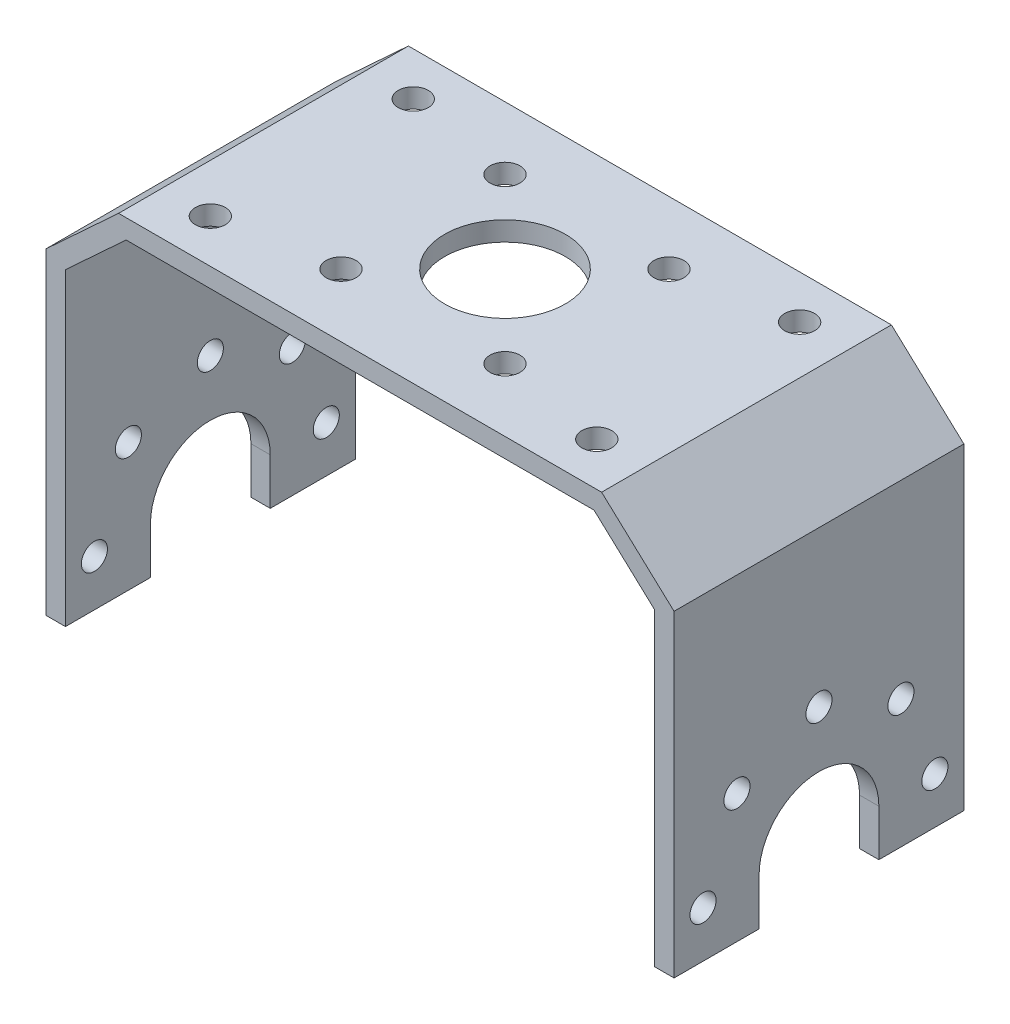
SolidWorks part; units mm, degrees
ref_plane "Plan de face" through (0, 0, 0) normal (0, 0, 1) x (1, 0, 0)
ref_plane "Plan de dessus" through (0, 0, 0) normal (0, 1, 0) x (1, 0, 0)
ref_plane "Plan de droite" through (0, 0, 0) normal (1, 0, 0) x (0, 0, -1)
sketch "Esquisse1" plane through (0, 0, 0) normal (0, 0, 1) x (1, 0, 0)
  line L0 (0, 0) -> (0, 39.8) construction
  line L1 (-25, 39.8) -> (25, 39.8)
  line L2 (25, 39.8) -> (32.5, 32.8755)
  line L3 (32.5, 32.8755) -> (32.5, 0)
  line L4 (32.5, 0) -> (30.5, 0)
  line L5 (30.5, 0) -> (30.5, 32)
  line L6 (30.5, 32) -> (24.2179, 37.8)
  line L7 (24.2179, 37.8) -> (-24.2179, 37.8)
  line L8 (-30.5, 32) -> (-24.2179, 37.8)
  line L9 (-30.5, 0) -> (-30.5, 32)
  line L10 (-32.5, 0) -> (-30.5, 0)
  line L11 (-32.5, 32.8755) -> (-32.5, 0)
  line L12 (-25, 39.8) -> (-32.5, 32.8755)
  point P11 (0, 37.8)
  dimension "D1" = 2
  dimension "D2" = 39.8
  dimension "D3" = 2
  dimension "D4" = 2
  dimension "D5" = 65
  dimension "D6" = 32
  dimension "D7" = 50
extrude "Boss.-Extru.1" add sketch "Esquisse1" along normal mid plane 30
sketch "Esquisse3" plane through (0, 39.8, 0) normal (0, 1, 0) x (1, 0, 0)
  line L0 (0, 0) -> (0, 15) construction
  line L1 (-8.4853, -8.4853) -> (8.4853, -8.4853) construction
  line L2 (-8.4853, -8.4853) -> (-8.4853, 8.4853) construction
  line L3 (-8.4853, 8.4853) -> (8.4853, 8.4853) construction
  line L4 (8.4853, -8.4853) -> (8.4853, 8.4853) construction
  line L5 (25, 15) -> (-25, 15) construction
  line L6 (0, 0) -> (25, 0) construction
  line L7 (25, -15) -> (25, 15) construction
  circle A0 centre (0, 0) radius 6.25
  circle A1 centre (0, 0) radius 12 construction
  circle A2 centre (-8.4853, 8.4853) radius 1.55
  circle A3 centre (-8.4853, -8.4853) radius 1.55
  circle A4 centre (8.4853, -8.4853) radius 1.55
  circle A5 centre (8.4853, 8.4853) radius 1.55
  circle A6 centre (20, 10.5) radius 1.55
  circle A7 centre (-20, 10.5) radius 1.55
  circle A8 centre (20, -10.5) radius 1.55
  circle A9 centre (-20, -10.5) radius 1.55
  dimension "D1" = 12.5
  dimension "D2" = 3.1
  dimension "D3" = 24
  dimension "D4" = 21
  dimension "D5" = 40
extrude "Enlèv. mat.-Extru.1" cut sketch "Esquisse3" against normal through all
sketch "Esquisse4" plane through (32.5, 0, 0) normal (1, 0, 0) x (0, 0, -1)
  line L0 (0, 0) -> (0, 4.8) construction
  line L1 (-6.2, 0) -> (-6.2, 4.8)
  line L2 (-15, 0) -> (15, 0) construction
  line L3 (6.2, 4.8) -> (6.2, 0)
  line L4 (-6.2, 0) -> (6.2, 0)
  line L5 (-6, 10.8) -> (-8.4853, 13.2853) construction
  line L6 (0, 4.8) -> (0, 16.8) construction
  line L7 (0, 16.8) -> (-12, 4.8) construction
  arc A0 (-6.2, 4.8) -> (6.2, 4.8) centre (0, 4.8) cw
  circle A1 centre (0, 4.8) radius 12 construction
  circle A2 centre (-12, 4.8) radius 1.35
  circle A3 centre (0, 16.8) radius 1.35
  circle A4 centre (-8.4853, 13.2853) radius 1.35
  circle A5 centre (12, 4.8) radius 1.35
  circle A6 centre (8.4853, 13.2853) radius 1.35
  point P8 (0, 11)
  dimension "D1" = 6.2
  dimension "D3" = 24
  dimension "D4" = 2.7
  dimension "D2" = 11
extrude "Enlèv. mat.-Extru.2" cut sketch "Esquisse4" against normal through all
equation "\"D3@Esquisse1\"=\"D1@Esquisse1\""
equation "\"D4@Esquisse1\"=\"D1@Esquisse1\""
